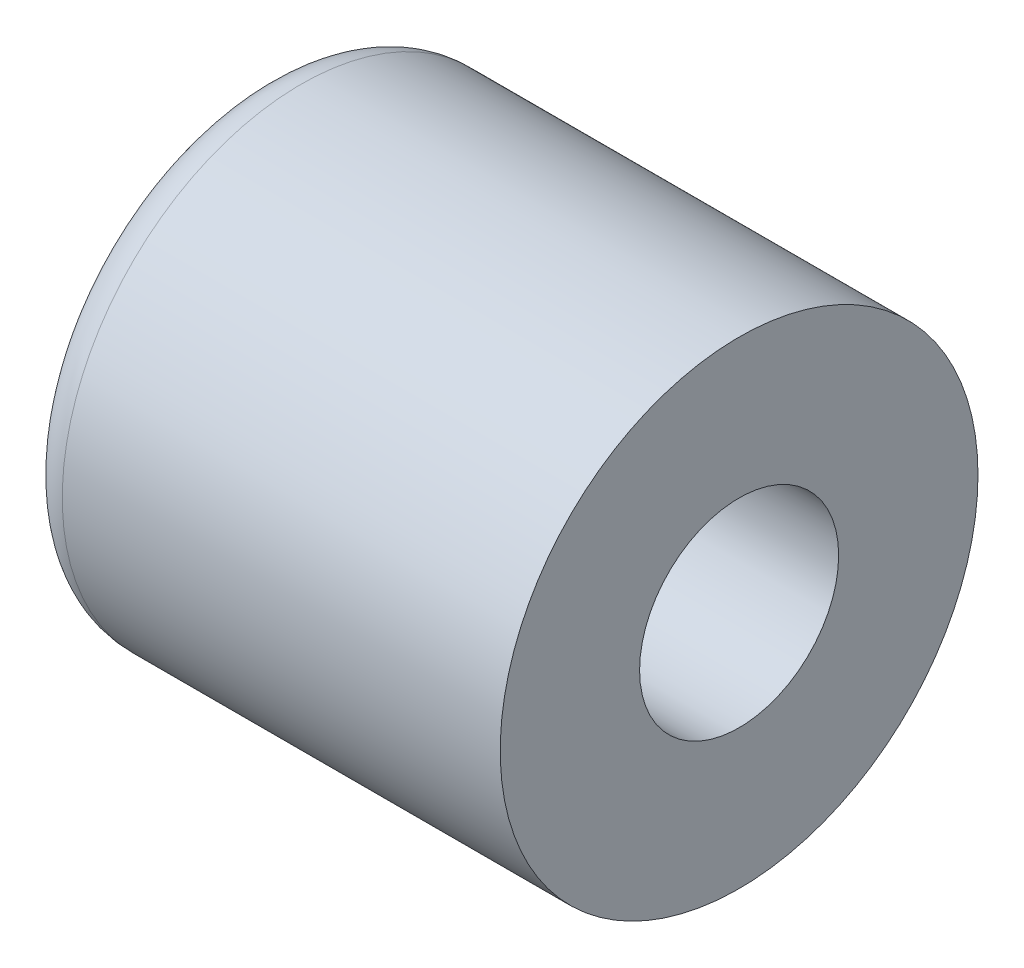
SolidWorks part; units mm, degrees
ref_plane "Front Plane" through (0, 0, 0) normal (0, 0, 1) x (1, 0, 0)
ref_plane "Top Plane" through (0, 0, 0) normal (0, 1, 0) x (1, 0, 0)
ref_plane "Right Plane" through (0, 0, 0) normal (1, 0, 0) x (0, 0, -1)
sketch "Sketch1" plane through (0, 0, 0) normal (1, 0, 0) x (0, 0, -1)
  circle A0 centre (0, 0) radius 6
  circle A1 centre (0, 0) radius 2.5
  dimension "D1" = 12
  dimension "D2" = 5
extrude "Boss-Extrude1" add sketch "Sketch1" along normal blind 12
fillet "Fillet1" radius 1 1 edges at (0, 0, -6)
